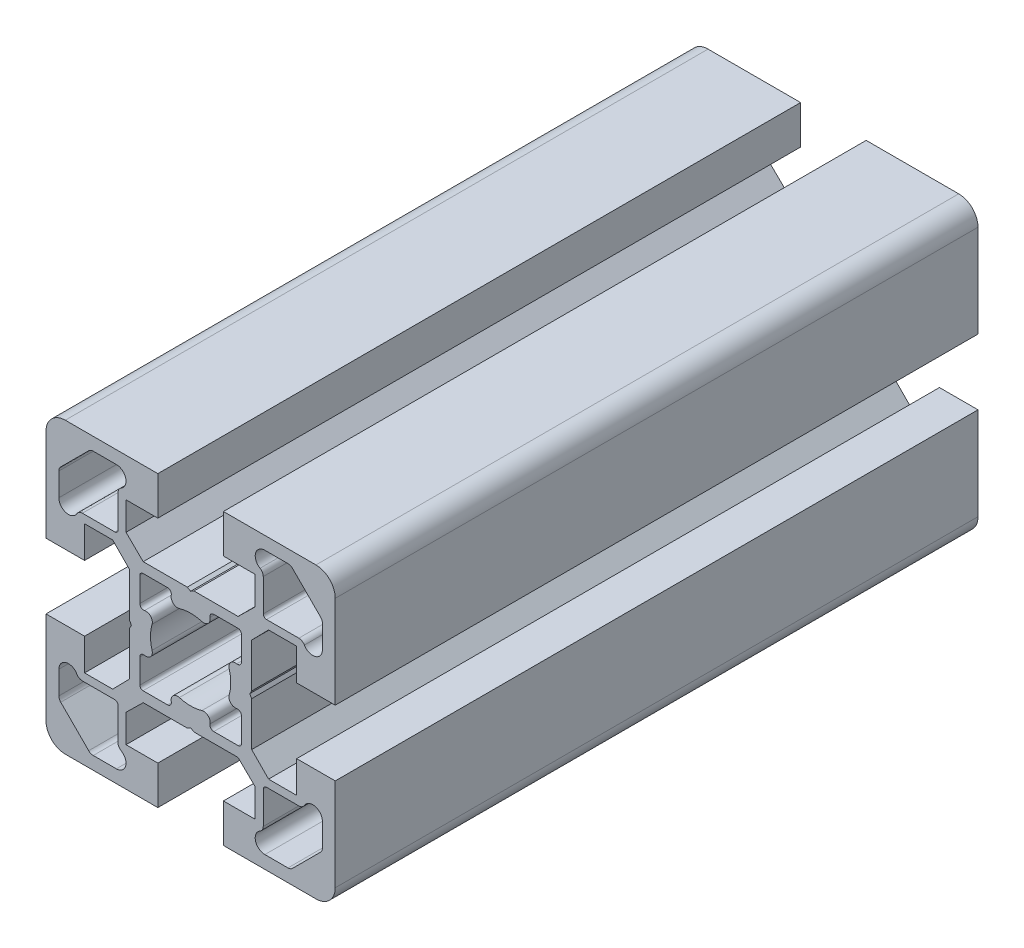
SolidWorks part; units mm, degrees
material "6063-T5"
ref_plane "Plan de face" through (0, 0, 0) normal (0, 0, 1) x (1, 0, 0)
ref_plane "Plan de dessus" through (0, 0, 0) normal (0, 1, 0) x (1, 0, 0)
ref_plane "Plan de droite" through (0, 0, 0) normal (1, 0, 0) x (0, 0, -1)
sketch "Esquisse1" plane through (0, 0, 0) normal (0, 0, 1) x (1, 0, 0)
  line L0 (15.8553, -20.2071) -> (20.2071, -15.8553)
  line L1 (20.5, -15.1482) -> (20.5, -11.55)
  line L2 (16.8349, -11.3) -> (11.8, -11.3)
  line L3 (11.3, -11.8) -> (11.3, -16.8349)
  line L4 (11.55, -20.5) -> (15.1482, -20.5)
  line L5 (-20.5, -11.55) -> (-20.5, -15.1482)
  line L6 (-20.2071, -15.8553) -> (-15.8553, -20.2071)
  line L7 (-15.1482, -20.5) -> (-11.55, -20.5)
  line L8 (-11.3, -16.8349) -> (-11.3, -11.8)
  line L9 (-11.8, -11.3) -> (-16.8349, -11.3)
  line L10 (-15.8553, 20.2071) -> (-20.2071, 15.8553)
  line L11 (-20.5, 15.1482) -> (-20.5, 11.55)
  line L12 (-16.8349, 11.3) -> (-11.8, 11.3)
  line L13 (-11.3, 11.8) -> (-11.3, 16.8349)
  line L14 (-11.55, 20.5) -> (-15.1482, 20.5)
  line L15 (-3.6, 7.9) -> (-7.4, 7.9)
  line L16 (-7.9, 7.4) -> (-7.9, 3.6)
  line L17 (-7.9, -3.6) -> (-7.9, -7.4)
  line L18 (-7.4, -7.9) -> (-3.6, -7.9)
  line L19 (3.6, -7.9) -> (7.4, -7.9)
  line L20 (7.9, -7.4) -> (7.9, -3.6)
  line L21 (7.9, 3.6) -> (7.9, 7.4)
  line L22 (7.4, 7.9) -> (3.6, 7.9)
  line L23 (11.3, 16.8349) -> (11.3, 11.8)
  line L24 (11.8, 11.3) -> (16.8349, 11.3)
  line L25 (20.5, 11.55) -> (20.5, 15.1482)
  line L26 (20.2071, 15.8553) -> (15.8553, 20.2071)
  line L27 (15.1482, 20.5) -> (11.55, 20.5)
  line L28 (22.5, 5.1) -> (22.5, 19.5)
  line L29 (16.5, 5.1) -> (22.5, 5.1)
  line L30 (16.5, 10.05) -> (16.5, 5.1)
  line L31 (12.1213, 10.05) -> (16.5, 10.05)
  line L32 (9.5, 7.3787) -> (12.1213, 10.05)
  line L33 (9.5, 0.5196) -> (9.5, 7.3787)
  line L34 (9.2, 0) -> (9.5, 0.5196)
  line L35 (9.5, -0.5196) -> (9.2, 0)
  line L36 (9.5, -7.3787) -> (9.5, -0.5196)
  line L37 (12.1213, -10.05) -> (9.5, -7.3787)
  line L38 (16.5, -10.05) -> (12.1213, -10.05)
  line L39 (16.5, -5.1) -> (16.5, -10.05)
  line L40 (22.5, -5.1) -> (16.5, -5.1)
  line L41 (22.5, -19.5) -> (22.5, -5.1)
  line L42 (5.1, -22.5) -> (19.5, -22.5)
  line L43 (5.1, -16.5) -> (5.1, -22.5)
  line L44 (10.05, -16.5) -> (5.1, -16.5)
  line L45 (10.05, -12.1213) -> (10.05, -16.5)
  line L46 (7.3787, -9.5) -> (10.05, -12.1213)
  line L47 (0.5196, -9.5) -> (7.3787, -9.5)
  line L48 (0, -9.2) -> (0.5196, -9.5)
  line L49 (-0.5196, -9.5) -> (0, -9.2)
  line L50 (-7.3787, -9.5) -> (-0.5196, -9.5)
  line L51 (-10.05, -12.1213) -> (-7.3787, -9.5)
  line L52 (-10.05, -16.5) -> (-10.05, -12.1213)
  line L53 (-5.1, -16.5) -> (-10.05, -16.5)
  line L54 (-5.1, -22.5) -> (-5.1, -16.5)
  line L55 (-19.5, -22.5) -> (-5.1, -22.5)
  line L56 (-22.5, -5.1) -> (-22.5, -19.5)
  line L57 (-16.5, -5.1) -> (-22.5, -5.1)
  line L58 (-16.5, -10.05) -> (-16.5, -5.1)
  line L59 (-12.1213, -10.05) -> (-16.5, -10.05)
  line L60 (-9.5, -7.3787) -> (-12.1213, -10.05)
  line L61 (-9.5, -0.5196) -> (-9.5, -7.3787)
  line L62 (-9.2, 0) -> (-9.5, -0.5196)
  line L63 (-9.5, 0.5196) -> (-9.2, 0)
  line L64 (-9.5, 7.3787) -> (-9.5, 0.5196)
  line L65 (-12.1213, 10.05) -> (-9.5, 7.3787)
  line L66 (-16.5, 10.05) -> (-12.1213, 10.05)
  line L67 (-16.5, 5.1) -> (-16.5, 10.05)
  line L68 (-22.5, 5.1) -> (-16.5, 5.1)
  line L69 (-22.5, 19.5) -> (-22.5, 5.1)
  line L70 (-5.1, 22.5) -> (-19.5, 22.5)
  line L71 (-5.1, 16.5) -> (-5.1, 22.5)
  line L72 (-10.05, 16.5) -> (-5.1, 16.5)
  line L73 (-10.05, 12.1213) -> (-10.05, 16.5)
  line L74 (-7.3787, 9.5) -> (-10.05, 12.1213)
  line L75 (-0.5196, 9.5) -> (-7.3787, 9.5)
  line L76 (0, 9.2) -> (-0.5196, 9.5)
  line L77 (0.5196, 9.5) -> (0, 9.2)
  line L78 (7.3787, 9.5) -> (0.5196, 9.5)
  line L79 (10.05, 12.1213) -> (7.3787, 9.5)
  line L80 (10.05, 16.5) -> (10.05, 12.1213)
  line L81 (5.1, 16.5) -> (10.05, 16.5)
  line L82 (5.1, 22.5) -> (5.1, 16.5)
  line L83 (19.5, 22.5) -> (5.1, 22.5)
  arc A0 (15.1482, -20.5) -> (15.8553, -20.2071) centre (15.1482, -19.5) ccw
  arc A1 (20.2071, -15.8553) -> (20.5, -15.1482) centre (19.5, -15.1482) ccw
  arc A2 (20.5, -11.55) -> (17.701, -10.8) centre (19, -11.55) ccw
  arc A3 (16.8349, -11.3) -> (17.701, -10.8) centre (16.8349, -10.3) ccw
  arc A4 (11.8, -11.3) -> (11.3, -11.8) centre (11.8, -11.8) ccw
  arc A5 (10.8, -17.701) -> (11.3, -16.8349) centre (10.3, -16.8349) ccw
  arc A6 (10.8, -17.701) -> (11.55, -20.5) centre (11.55, -19) ccw
  arc A7 (-17.701, -10.8) -> (-16.8349, -11.3) centre (-16.8349, -10.3) ccw
  arc A8 (-17.701, -10.8) -> (-20.5, -11.55) centre (-19, -11.55) ccw
  arc A9 (-20.5, -15.1482) -> (-20.2071, -15.8553) centre (-19.5, -15.1482) ccw
  arc A10 (-15.8553, -20.2071) -> (-15.1482, -20.5) centre (-15.1482, -19.5) ccw
  arc A11 (-11.55, -20.5) -> (-10.8, -17.701) centre (-11.55, -19) ccw
  arc A12 (-11.3, -16.8349) -> (-10.8, -17.701) centre (-10.3, -16.8349) ccw
  arc A13 (-11.3, -11.8) -> (-11.8, -11.3) centre (-11.8, -11.8) ccw
  arc A14 (-15.1482, 20.5) -> (-15.8553, 20.2071) centre (-15.1482, 19.5) ccw
  arc A15 (-20.2071, 15.8553) -> (-20.5, 15.1482) centre (-19.5, 15.1482) ccw
  arc A16 (-20.5, 11.55) -> (-17.701, 10.8) centre (-19, 11.55) ccw
  arc A17 (-16.8349, 11.3) -> (-17.701, 10.8) centre (-16.8349, 10.3) ccw
  arc A18 (-11.8, 11.3) -> (-11.3, 11.8) centre (-11.8, 11.8) ccw
  arc A19 (-10.8, 17.701) -> (-11.3, 16.8349) centre (-10.3, 16.8349) ccw
  arc A20 (-10.8, 17.701) -> (-11.55, 20.5) centre (-11.55, 19) ccw
  arc A21 (3.6, 7.9) -> (3.0139, 7.1717) centre (3.6, 7.3) ccw
  arc A22 (1.756, 5.9982) -> (3.0139, 7.1717) centre (2.037, 6.958) ccw
  arc A23 (1.756, 5.9982) -> (-1.756, 5.9982) centre (0, 0) ccw
  arc A24 (-3.0139, 7.1717) -> (-1.756, 5.9982) centre (-2.037, 6.958) ccw
  arc A25 (-3.0139, 7.1717) -> (-3.6, 7.9) centre (-3.6, 7.3) ccw
  arc A26 (-7.4, 7.9) -> (-7.9, 7.4) centre (-7.4, 7.4) ccw
  arc A27 (-7.9, 3.6) -> (-7.1717, 3.0139) centre (-7.3, 3.6) ccw
  arc A28 (-5.9982, 1.756) -> (-7.1717, 3.0139) centre (-6.958, 2.037) ccw
  arc A29 (-5.9982, 1.756) -> (-5.9982, -1.756) centre (0, 0) ccw
  arc A30 (-7.1717, -3.0139) -> (-5.9982, -1.756) centre (-6.958, -2.037) ccw
  arc A31 (-7.1717, -3.0139) -> (-7.9, -3.6) centre (-7.3, -3.6) ccw
  arc A32 (-7.9, -7.4) -> (-7.4, -7.9) centre (-7.4, -7.4) ccw
  arc A33 (-3.6, -7.9) -> (-3.0139, -7.1717) centre (-3.6, -7.3) ccw
  arc A34 (-1.756, -5.9982) -> (-3.0139, -7.1717) centre (-2.037, -6.958) ccw
  arc A35 (-1.756, -5.9982) -> (1.756, -5.9982) centre (0, 0) ccw
  arc A36 (3.0139, -7.1717) -> (1.756, -5.9982) centre (2.037, -6.958) ccw
  arc A37 (3.0139, -7.1717) -> (3.6, -7.9) centre (3.6, -7.3) ccw
  arc A38 (7.4, -7.9) -> (7.9, -7.4) centre (7.4, -7.4) ccw
  arc A39 (7.9, -3.6) -> (7.1717, -3.0139) centre (7.3, -3.6) ccw
  arc A40 (5.9982, -1.756) -> (7.1717, -3.0139) centre (6.958, -2.037) ccw
  arc A41 (5.9982, -1.756) -> (5.9982, 1.756) centre (0, 0) ccw
  arc A42 (7.1717, 3.0139) -> (5.9982, 1.756) centre (6.958, 2.037) ccw
  arc A43 (7.1717, 3.0139) -> (7.9, 3.6) centre (7.3, 3.6) ccw
  arc A44 (7.9, 7.4) -> (7.4, 7.9) centre (7.4, 7.4) ccw
  arc A45 (11.55, 20.5) -> (10.8, 17.701) centre (11.55, 19) ccw
  arc A46 (11.3, 16.8349) -> (10.8, 17.701) centre (10.3, 16.8349) ccw
  arc A47 (11.3, 11.8) -> (11.8, 11.3) centre (11.8, 11.8) ccw
  arc A48 (17.701, 10.8) -> (16.8349, 11.3) centre (16.8349, 10.3) ccw
  arc A49 (17.701, 10.8) -> (20.5, 11.55) centre (19, 11.55) ccw
  arc A50 (20.5, 15.1482) -> (20.2071, 15.8553) centre (19.5, 15.1482) ccw
  arc A51 (15.8553, 20.2071) -> (15.1482, 20.5) centre (15.1482, 19.5) ccw
  arc A52 (19.5, -22.5) -> (22.5, -19.5) centre (19.5, -19.5) ccw
  arc A53 (-22.5, -19.5) -> (-19.5, -22.5) centre (-19.5, -19.5) ccw
  arc A54 (-19.5, 22.5) -> (-22.5, 19.5) centre (-19.5, 19.5) ccw
  arc A55 (22.5, 19.5) -> (19.5, 22.5) centre (19.5, 19.5) ccw
extrude "Boss.-Extru.1" add sketch "Esquisse1" along normal blind 100
